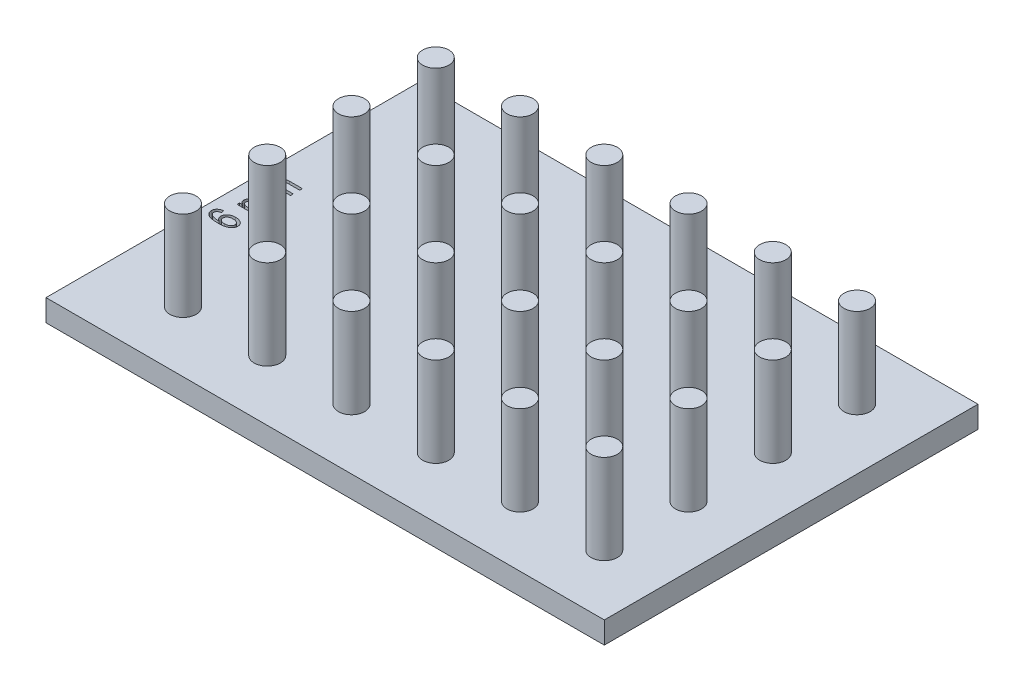
SolidWorks part; units mm, degrees
material "PVC Rigid"
ref_plane "Front Plane" through (0, 0, 0) normal (0, 0, 1) x (1, 0, 0)
ref_plane "Top Plane" through (0, 0, 0) normal (0, 1, 0) x (1, 0, 0)
ref_plane "Right Plane" through (0, 0, 0) normal (1, 0, 0) x (0, 0, -1)
ref_plane "Top of 24 well plate" through (0, 6, 0) normal (0, 1, 0) x (1, 0, 0)
ref_plane "Bottom of 24 well plate" through (0, 23.5, 0) normal (0, 1, 0) x (1, 0, 0)
sketch "Sketch1" plane through (0, 0, 0) normal (0, 1, 0) x (1, 0, 0)
  line L1 (-63.945, 42.8) -> (63.945, 42.8)
  line L2 (-63.945, 42.8) -> (-63.945, -42.8)
  line L3 (-63.945, -42.8) -> (63.945, -42.8)
  line L4 (63.945, 42.8) -> (63.945, -42.8)
  line L5 (-63.945, 42.8) -> (63.945, -42.8) construction
  line L6 (-63.945, -42.8) -> (63.945, 42.8) construction
  point P0 (0, 0)
  dimension "D1" = 127.89
  dimension "D2" = 85.6
ref_plane "Middle of 24 well plate" through (0, 14.75, 0) normal (0, 1, 0) x (1, 0, 0)
sketch "Wells_LSP" plane through (0, 0, 0) normal (0, 1, 0) x (1, 0, 0)
  line L0 (-46.425, 28.96) -> (-27.125, 28.96) construction
  line L1 (-63.945, 42.8) -> (63.945, 42.8) construction
  line L2 (-63.945, 42.8) -> (-63.945, -42.8) construction
  circle A0 centre (-46.425, 28.96) radius 7.81
  circle A1 centre (-27.125, 28.96) radius 7.81
  circle A2 centre (-7.825, 28.96) radius 7.81
  circle A3 centre (11.475, 28.96) radius 7.81
  circle A4 centre (30.775, 28.96) radius 7.81
  circle A5 centre (50.075, 28.96) radius 7.81
  circle A6 centre (-27.125, 9.66) radius 7.81
  circle A7 centre (-7.825, 9.66) radius 7.81
  circle A8 centre (11.475, 9.66) radius 7.81
  circle A9 centre (30.775, 9.66) radius 7.81
  circle A10 centre (50.075, 9.66) radius 7.81
  circle A11 centre (-27.125, -9.64) radius 7.81
  circle A12 centre (-7.825, -9.64) radius 7.81
  circle A13 centre (11.475, -9.64) radius 7.81
  circle A14 centre (30.775, -9.64) radius 7.81
  circle A15 centre (50.075, -9.64) radius 7.81
  circle A16 centre (-27.125, -28.94) radius 7.81
  circle A17 centre (-7.825, -28.94) radius 7.81
  circle A18 centre (11.475, -28.94) radius 7.81
  circle A19 centre (30.775, -28.94) radius 7.81
  circle A20 centre (50.075, -28.94) radius 7.81
  circle A21 centre (-46.425, 9.66) radius 7.81
  circle A22 centre (-46.425, -9.64) radius 7.81
  circle A23 centre (-46.425, -28.94) radius 7.81
  dimension "D2" = 6
  dimension "D4" = 4
  dimension "D7" = 15.62
  dimension "D3" = 19.3
  dimension "D5" = 13.84
  dimension "D6" = 17.52
ref_plane "Plane1" through (0, 0, -28.96) normal (0, 0, 1) x (1, 0, 0)
sketch "Sketch2" plane through (0, 0, -28.96) normal (0, 0, 1) x (1, 0, 0)
  line L0 (50.075, 14.75) -> (50.075, 0) construction
  line L1 (50.075, 20.5) -> (53.075, 20.5)
  line L2 (50.075, 20.5) -> (50.075, 0)
  line L3 (50.075, 0) -> (53.075, 0)
  line L4 (53.075, 20.5) -> (53.075, 0)
  line L5 (55, 6) -> (-55, 6) construction
  line L8 (55, 14.75) -> (-55, 14.75) construction
  line L9 (55, 23.5) -> (-55, 23.5) construction
  line L10 (-63.945, 0) -> (63.945, 0) construction
  point P10 (53.075, 6)
  point P13 (50.075, 14.75)
  dimension "D1" = 0
  dimension "D2" = 3
  dimension "D3" = 3
revolve "Revolve1" add sketch "Sketch2" angle 360 about L2
extrude "Boss-Extrude2" add sketch "Sketch1" against normal blind 5
pattern_linear "LPattern2" count 4 spacing 19.3 along (0, 0, 1) count 6 spacing 19.3 along (-1, 0, 0) of "Revolve1"
sketch "Sketch5" plane through (0, 0, 0) normal (0, 1, 0) x (1, 0, 0)
  line L0 (-56.1948, 42.8) -> (-56.1948, -42.8) construction
  line L1 (63.945, 42.8) -> (-63.945, 42.8) construction
  line L2 (-63.945, -42.8) -> (63.945, -42.8) construction
  text T0 "6 mm" font "Arial Narrow" height 6
extrude "Cut-Extrude1" cut sketch "Sketch5" against normal blind 2
equation "\"D1\"= 0.32"
equation "\"D1\"= 1.27 - 0.32"
